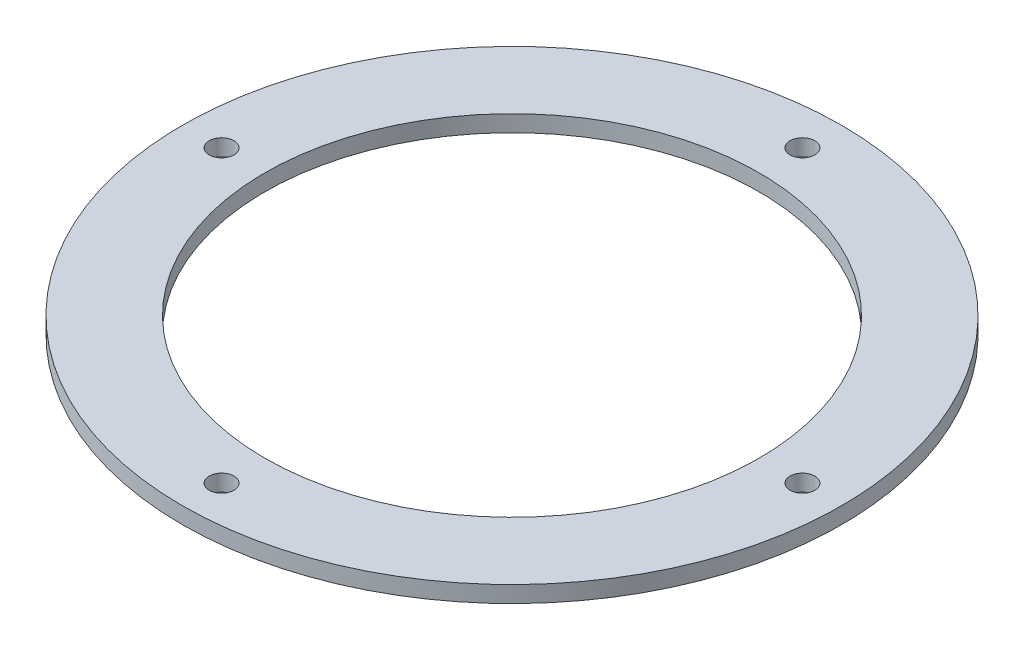
SolidWorks part; units mm, degrees
ref_plane "Alzado" through (0, 0, 0) normal (0, 0, 1) x (1, 0, 0)
ref_plane "Planta" through (0, 0, 0) normal (0, 1, 0) x (1, 0, 0)
ref_plane "Vista lateral" through (0, 0, 0) normal (1, 0, 0) x (0, 0, -1)
sketch "Croquis base" plane through (0, 0, 0) normal (0, 1, 0) x (1, 0, 0)
  circle A0 centre (0, 0) radius 40
  circle A1 centre (0, 0) radius 30
extrude "Saliente-Extruir1" add sketch "Croquis base" along normal blind 2
sketch "Croquis Barrenos" plane through (0, 2, 0) normal (0, 1, 0) x (1, 0, 0)
  line L0 (-35.25, 0) -> (0, 0) construction
  circle A0 centre (0, 0) radius 35.25 construction
  circle A1 centre (-35.25, 0) radius 1.5
  circle A2 centre (0, 35.25) radius 1.5
  circle A3 centre (35.25, 0) radius 1.5
  circle A4 centre (0, -35.25) radius 1.5
  dimension "D1" = 4
extrude "Cortar-Extruir1" cut sketch "Croquis Barrenos" against normal blind 2
